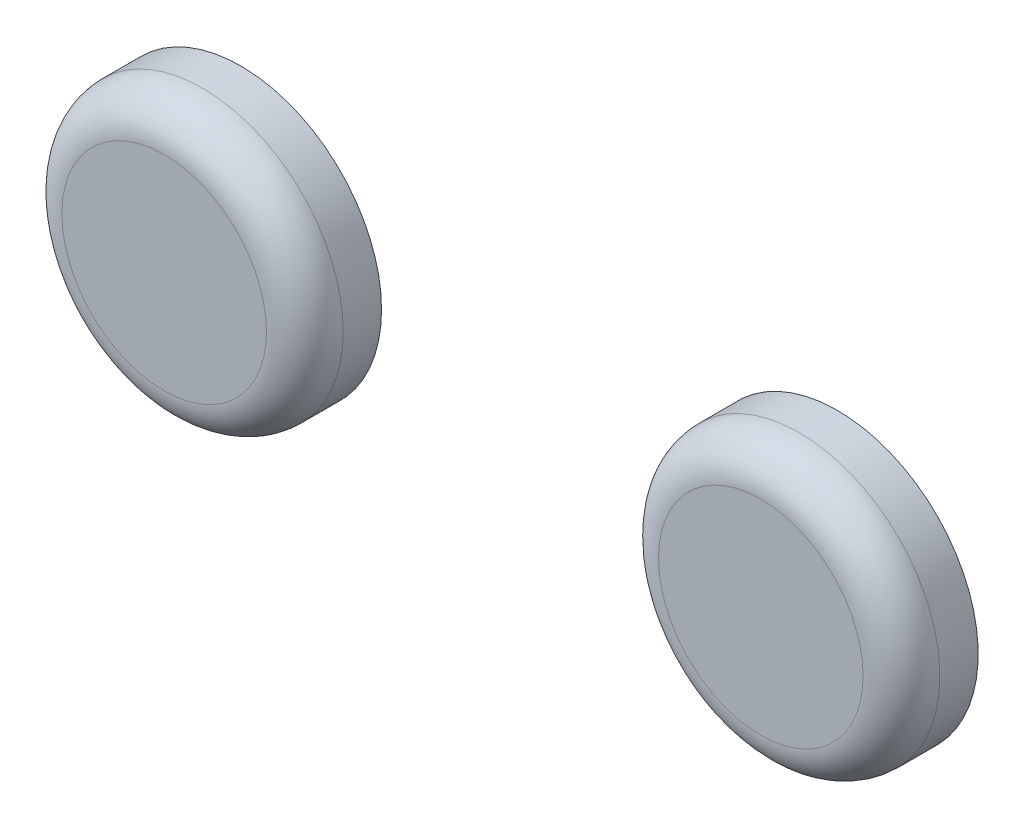
SolidWorks part; units mm, degrees
other "DetailItem3"
other "DetailItem4"
ref_plane "Front Plane" through (0, 0, 0) normal (0, 0, 1) x (1, 0, 0)
ref_plane "Top Plane" through (0, 0, 0) normal (0, 1, 0) x (1, 0, 0)
ref_plane "Right Plane" through (0, 0, 0) normal (1, 0, 0) x (0, 0, -1)
sketch "Sketch1" plane through (0, 0, 0) normal (0, 0, 1) x (1, 0, 0)
  line L0 (0, 86.9262) -> (0, -53.0738) construction
  line L1 (-70, 0) -> (70, 0) construction
  line L2 (-70, 53.0738) -> (-70, -53.0738) construction
  line L3 (70, 53.0738) -> (70, -53.0738) construction
  circle A0 centre (-70, 0) radius 33
  circle A1 centre (70, 0) radius 33
  point P3 (-68.9342, 0)
  point P4 (0, 0)
  point P10 (0, 0)
  dimension "D1" = 66
  dimension "D2" = 140
extrude "Boss-Extrude1" add sketch "Sketch1" along normal blind 18
fillet "Fillet1" radius 9 1 edges at (-37, 0, 18)
fillet "Fillet2" radius 9 1 edges at (37, 0, 18)
